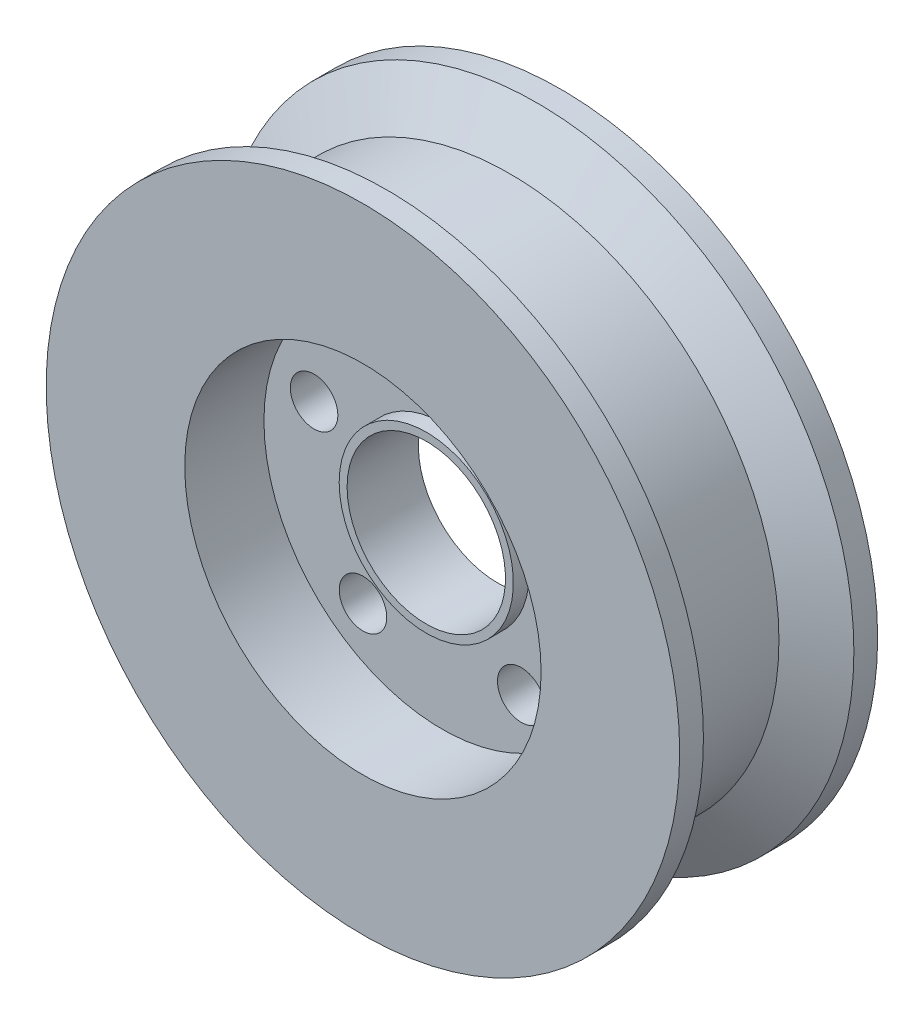
SolidWorks part; units mm, degrees
ref_plane "Front Plane" through (0, 0, 0) normal (0, 0, 1) x (1, 0, 0)
ref_plane "Top Plane" through (0, 0, 0) normal (0, 1, 0) x (1, 0, 0)
ref_plane "Right Plane" through (0, 0, 0) normal (1, 0, 0) x (0, 0, -1)
sketch "Sketch1" plane through (0, 0, 0) normal (0, 0, 1) x (1, 0, 0)
  circle A0 centre (0, 0) radius 10
  circle A1 centre (0, 0) radius 40
  dimension "D1" = 80
  dimension "D2" = 20
extrude "Boss-Extrude1" add sketch "Sketch1" along normal mid plane 25
sketch "Sketch2" plane through (0, 0, 12.5) normal (0, 0, 1) x (1, 0, 0)
  circle A0 centre (0, 0) radius 22.5
  circle A1 centre (0, 0) radius 40 construction
  dimension "D1" = 17.5
extrude "Cut-Extrude1" cut sketch "Sketch2" against normal blind 10
mirror "Mirror1" about plane through (0, 0, 0) normal (0, 0, 1) of "Cut-Extrude1"
sketch "Sketch3" plane through (0, 0, 2.5) normal (0, 0, 1) x (1, 0, 0)
  circle A0 centre (0, 17) radius 3
  dimension "D1" = 6
  dimension "D2" = 17
extrude "Cut-Extrude2" cut sketch "Sketch3" against normal through all
pattern_circular "CirPattern1" count 5 over 360 about axis through (0, 0, 0) along (0, 0, 1) of "Cut-Extrude2"
sketch "Sketch4" plane through (0, 0, -2.5) normal (0, 0, -1) x (-1, 0, 0)
  circle A0 centre (0, 0) radius 10 construction
  circle A1 centre (0, 0) radius 10
  circle A2 centre (0, 0) radius 11
  dimension "D1" = 22
extrude "Boss-Extrude2" add sketch "Sketch4" along normal blind 2 and the other way blind 7
sketch "Sketch5" plane through (0, 0, 0) normal (0, 1, 0) x (1, 0, 0)
  line L0 (0, 0) -> (0, 27.5874) construction
  line L1 (-40, 9.5) -> (-34, 6.0359)
  line L2 (-40, 12.5) -> (-40, -12.5) construction
  line L3 (-34, 6.0359) -> (-34, -6.0359)
  line L4 (-34, -6.0359) -> (-40, -9.5)
  line L5 (-40, -9.5) -> (-40, 9.5)
  line L6 (40, 12.5) -> (-40, 12.5) construction
  line L7 (-40, -12.5) -> (40, -12.5) construction
  dimension "D1" = 3
  dimension "D2" = 3
  dimension "D3" = 60
  dimension "D4" = 6
  dimension "D5" = 60
revolve "Cut-Revolve1" cut sketch "Sketch5" angle 360 about L0
